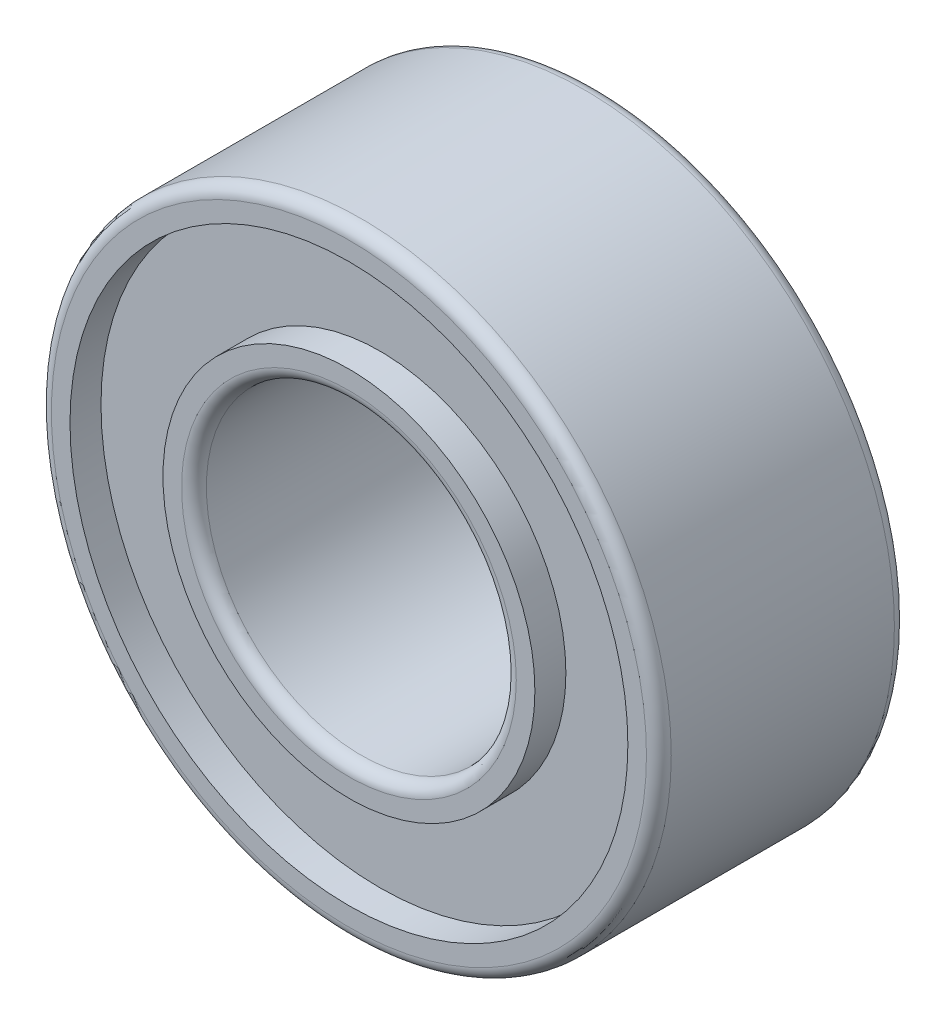
SolidWorks part; units mm, degrees
ref_plane "Ebene vorne" through (0, 0, 0) normal (0, 0, 1) x (1, 0, 0)
ref_plane "Ebene oben" through (0, 0, 0) normal (0, 1, 0) x (1, 0, 0)
ref_plane "Ebene rechts" through (0, 0, 0) normal (1, 0, 0) x (0, 0, -1)
sketch "Skizze1" plane through (0, 0, 0) normal (0, 0, 1) x (1, 0, 0)
  circle A0 centre (0, 0) radius 5
  circle A1 centre (0, 0) radius 2.5
extrude "Aufsatz-Linear austragen1" add sketch "Skizze1" along normal blind 4
fillet "Verrundung1" radius 0.2 4 edges at (2.5, 0, 0) (5, 0, 0) (2.5, 0, 4) (5, 0, 4)
sketch "Skizze2" plane through (0, 0, 0) normal (0, 0, -1) x (-1, 0, 0)
  circle A0 centre (0, 0) radius 3
  circle A1 centre (0, 0) radius 4.5
  dimension "D1" = 9
  dimension "D2" = 6
extrude "Schnitt-Linear austragen1" cut sketch "Skizze2" against normal blind 0.5
sketch "Skizze3" plane through (0, 0, 4) normal (0, 0, 1) x (1, 0, 0)
  circle A0 centre (0, 0) radius 3
  circle A1 centre (0, 0) radius 4.5
extrude "Schnitt-Linear austragen2" cut sketch "Skizze3" against normal blind 0.5
